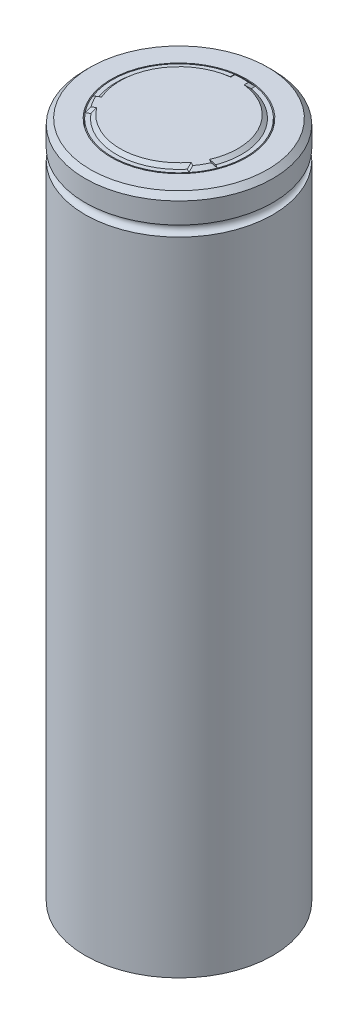
SolidWorks part; units mm, degrees
material "3003 Alloy"
ref_plane "Спереди" through (0, 0, 0) normal (0, 0, 1) x (1, 0, 0)
ref_plane "Сверху" through (0, 0, 0) normal (0, 1, 0) x (1, 0, 0)
ref_plane "Справа" through (0, 0, 0) normal (1, 0, 0) x (0, 0, -1)
sketch "Эскиз1" plane through (0, 0, 0) normal (0, 1, 0) x (1, 0, 0)
  circle A0 centre (0, 0) radius 9
  dimension "D1" = 18
extrude "Бобышка-Вытянуть1" add sketch "Эскиз1" along normal blind 65
sketch "Center" plane through (0, 0, 0) normal (0, 0, 1) x (1, 0, 0)
  line L0 (9, 65) -> (-9, 65) construction
  line L1 (0, 0) -> (0, 65) construction
  line L2 (-9, 0) -> (9, 0) construction
  point P6 (0, 32.5)
ref_plane "Midplane" through (0, 32.5, 0) normal (0, 1, 0) x (1, 0, 0)
sketch "Эскиз2" plane through (0, 0, 0) normal (0, 0, 1) x (1, 0, 0)
  line L0 (-9, 65) -> (-9, 0) construction
  line L1 (9, 65) -> (-9, 65) construction
  line L2 (0, 0) -> (0, 65) construction
  line L3 (-9, 0) -> (9, 0) construction
  circle A0 centre (-9, 62) radius 0.5
  dimension "D2" = 1
  dimension "D1" = 3
revolve "Вырез-Повернуть1" cut sketch "Эскиз2" angle 360 about L2
chamfer "Фаска1" distance 0.5 angle 45 1 edges at (0, 65, 9)
sketch "Эскиз3" plane through (0, 0, 0) normal (0, -1, 0) x (1, 0, 0)
  circle A0 centre (0, 0) radius 6.5
  circle A1 centre (0, 0) radius 6.4
  dimension "D1" = 13
  dimension "D2" = 0.1
extrude "Вырез-Вытянуть1" cut sketch "Эскиз3" against normal blind 65
sketch "Эскиз4" plane through (0, 65, 0) normal (0, 1, 0) x (1, 0, 0)
  line L0 (-1, 5.9161) -> (-1, 6.3214)
  line L1 (0, -9.9) -> (0, 9.9) construction
  line L2 (1, 5.9161) -> (1, 6.3214)
  line L3 (5.6235, -2.092) -> (5.9745, -2.2947)
  line L4 (4.6235, -3.8241) -> (4.9745, -4.0267)
  line L5 (-4.6235, -3.8241) -> (-4.9745, -4.0267)
  line L6 (-5.6235, -2.092) -> (-5.9745, -2.2947)
  arc A0 (-1, 5.9161) -> (-5.6235, -2.092) centre (0, 0) ccw
  circle A1 centre (0, 0) radius 6.4 construction
  arc A2 (1, 6.3214) -> (-1, 6.3214) centre (0, 0) ccw
  arc A3 (-5.9745, -2.2947) -> (-4.9745, -4.0267) centre (0, 0) ccw
  arc A4 (4.9745, -4.0267) -> (5.9745, -2.2947) centre (0, 0) ccw
  arc A5 (5.6235, -2.092) -> (1, 5.9161) centre (0, 0) ccw
  arc A6 (-4.6235, -3.8241) -> (4.6235, -3.8241) centre (0, 0) ccw
  point P21 (0, 0)
  dimension "D1" = 0.4053
  dimension "D2" = 1
  dimension "D4" = 1
  dimension "D5" = 1
extrude "Бобышка-Вытянуть2" add sketch "Эскиз4" along normal blind 0.3 draft 50
